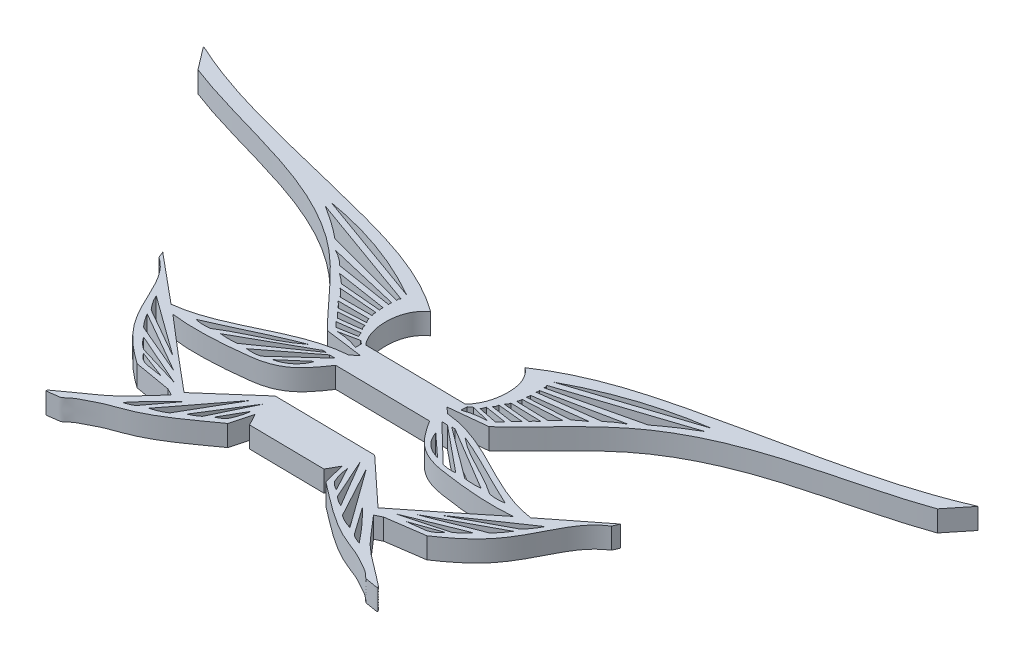
SolidWorks part; units mm, degrees
ref_plane "前视基准面" through (0, 0, 0) normal (0, 0, 1) x (1, 0, 0)
ref_plane "上视基准面" through (0, 0, 0) normal (0, 1, 0) x (1, 0, 0)
ref_plane "右视基准面" through (0, 0, 0) normal (1, 0, 0) x (0, 0, -1)
other "Configuration Table"
sketch "草图1" plane through (0, 0, 0) normal (0, 1, 0) x (1, 0, 0)
  line L0 (-16.1038, -29.8984) -> (-14.4909, -30.7553)
  line L1 (55.2168, 449.012) -> (841.2168, 449.012) construction
  line L2 (11.0888, 44.2891) -> (8.5696, -134.0017) construction
  line L3 (-35.1828, 28.1784) -> (-7.0967, 18.0952)
  line L4 (-27.2263, 21.1019) -> (-7.0967, 15.7486)
  line L6 (-21.1398, 16.1529) -> (-7.0967, 13.8965)
  line L7 (-24.774, 18.7977) -> (-7.2128, 14.6629)
  line L9 (-17.2033, 12.6101) -> (-7.0967, 11.7044)
  line L10 (-19.6184, 14.5422) -> (-7.2128, 12.6101)
  line L12 (-14.5684, 9.685) -> (-6.8789, 9.685)
  line L14 (-12.5975, 7.1733) -> (-6.0336, 7.5988)
  line L15 (-14.0695, 8.6454) -> (-6.577, 8.6454)
  line L17 (-10.5619, 5.0026) -> (-5.128, 5.6567)
  line L18 (-36.8477, -11.9893) -> (-22.4144, -22.4499)
  line L19 (-8.7638, 2.9366) -> (-4.2223, 3.7347)
  line L20 (-7.73, 2.2229) -> (-3.1356, 3.1712)
  line L21 (-16.4155, 11.532) -> (-7.0967, 10.7585)
  line L22 (-11.8701, 6.3108) -> (-5.6512, 6.7536)
  line L23 (-9.9443, 4.1171) -> (-4.6248, 4.8014)
  line L24 (-3.1356, 3.1712) -> (-2.3162, 2.539)
  line L25 (-2.3162, 2.539) -> (-2.3162, 1.0903)
  line L27 (-22.4144, -22.4499) -> (-34.4652, -15.5737)
  line L28 (-21.2778, -12.1694) -> (-5.6197, -3.4096)
  line L29 (-5.6197, -3.4096) -> (-4.7779, -3.4096)
  line L30 (-4.7779, -3.4096) -> (-17.294, -12.1857)
  line L32 (-15.0605, -12.1694) -> (-3.9079, -3.5602)
  line L33 (-3.9079, -3.5602) -> (-2.5338, -3.5602)
  line L34 (-2.5338, -3.5602) -> (-11.7753, -11.9893)
  line L35 (-9.6963, -11.3316) -> (-4.2223, -6.5835)
  line L36 (-34.191, -16.8125) -> (-19.1525, -25.4537)
  line L37 (-19.1525, -25.4537) -> (-31.8012, -20.077)
  line L38 (-29.805, -22.0591) -> (-16.8258, -27.7612)
  line L39 (-16.8258, -27.7612) -> (-27.2263, -24.6296)
  line L40 (-26.4037, -25.4537) -> (-19.6184, -28.0409)
  line L41 (-19.6184, -28.0409) -> (-23.7534, -27.401)
  line L42 (-3.9079, -22.4499) -> (-14.4158, -36.1706)
  line L43 (-16.4882, -37.1375) -> (-11.4591, -30.4187)
  line L44 (-8.6676, -32.8615) -> (-1.5765, -21.5816)
  line L45 (-4.7779, -30.2112) -> (-1.5765, -24.6296)
  line L46 (-6.3514, -31.4736) -> (-1.5765, -21.5816)
  line L47 (-10.9556, -34.6619) -> (-3.9079, -22.4499)
  line L48 (-45.0523, -2.2183) -> (-44.4505, -3.7232)
  line L49 (65.8936, -3.7859) -> (65.2495, -5.2733)
  line L50 (30.8938, -35.2532) -> (24.1939, -22.847)
  line L51 (26.3815, -31.9361) -> (21.8881, -21.9131)
  line L52 (24.8443, -30.6297) -> (21.8019, -24.9599)
  line L53 (28.6575, -33.3889) -> (21.8881, -21.9131)
  line L54 (36.3543, -37.8842) -> (31.5169, -31.026)
  line L55 (24.1939, -22.847) -> (34.31, -36.8591)
  line L56 (39.7402, -28.8797) -> (43.8916, -28.3568)
  line L57 (46.5959, -26.4851) -> (39.7402, -28.8797)
  line L58 (36.9566, -28.5211) -> (47.4415, -25.6846)
  line L59 (50.0918, -23.188) -> (36.9566, -28.5211)
  line L60 (39.3476, -26.2803) -> (52.1431, -21.2632)
  line L61 (54.6242, -18.0675) -> (39.3476, -26.2803)
  line L62 (30.2941, -11.8967) -> (24.9565, -6.9958)
  line L63 (23.3541, -3.926) -> (32.3538, -12.6128)
  line L64 (24.7277, -3.9648) -> (23.3541, -3.926)
  line L65 (35.6326, -12.8857) -> (24.7277, -3.9648)
  line L66 (25.6016, -3.8389) -> (37.8647, -12.9651)
  line L67 (26.4431, -3.8627) -> (25.6016, -3.8389)
  line L68 (41.8474, -13.0614) -> (26.4431, -3.8627)
  line L69 (42.6931, -23.3698) -> (54.9333, -16.8369)
  line L70 (23.309, 2.1769) -> (23.268, 0.7288)
  line L71 (24.1458, 2.7857) -> (23.309, 2.1769)
  line L72 (30.9785, 3.5389) -> (25.6806, 4.3732)
  line L73 (32.9655, 5.6773) -> (26.7617, 6.2956)
  line L74 (37.6567, 10.768) -> (28.3198, 10.2581)
  line L75 (28.7116, 1.708) -> (24.1458, 2.7857)
  line L76 (29.7652, 2.3922) -> (25.2481, 3.3183)
  line L77 (57.4161, -13.3212) -> (42.6931, -23.3698)
  line L78 (31.6209, 4.4066) -> (26.2077, 5.2139)
  line L79 (35.2301, 7.9488) -> (27.7406, 8.1605)
  line L80 (33.717, 6.5189) -> (27.1678, 7.1297)
  line L81 (35.7582, 8.9739) -> (28.0717, 9.1911)
  line L82 (40.9434, 13.6864) -> (28.4881, 12.1056)
  line L83 (38.4747, 11.8234) -> (28.3465, 11.2036)
  line L84 (46.2171, 17.7946) -> (28.5461, 14.1576)
  line L85 (42.5096, 15.2535) -> (28.4084, 13.3948)
  line L86 (48.7336, 20.0286) -> (28.4607, 15.2462)
  line L87 (56.8868, 26.8775) -> (28.527, 17.5919)
  line L88 (36.1745, -30.637) -> (34.538, -31.4481)
  line L89 (-1.5765, 2.8276) -> (22.5777, 2.4863)
  line L90 (-1.5765, -1.2849) -> (0, 0)
  line L91 (22.4615, -1.6245) -> (20.9219, -0.2956)
  line L92 (1.0655, -27.5848) -> (19.0775, -27.8393)
  line L93 (-1.5765, -1.2849) -> (-0.9859, -4.9581)
  line L94 (-0.9859, -4.9581) -> (21.7673, -5.2796)
  line L95 (-1.8489, -18.5408) -> (22.2462, -18.8813)
  spline S0 degree 3 poles (-0.7293, 17.4834) (-3.1453, 15.714) (-4.7785, 10.3382) (-3.3083, 4.8102) (-1.5765, 2.8276) knots 0 0 0 0 0.513587 1 1 1 1
  spline S1 degree 3 poles (-0.7293, 17.4834) (-9.9253, 24.1606) (-25.7873, 28.7225) (-53.9047, 35.5722) (-71.2957, 39.8733) (-82.7877, 45.2469) knots 0 0 0 0 0.38436 0.564437 1 1 1 1
  spline S2 degree 1 poles (-82.7877, 45.2469) (-78.5986, 39.7435) knots 0 0 1 1
  spline S3 degree 3 poles (-78.5986, 39.7435) (-66.4134, 35.0224) (-47.7039, 31.6735) (-23.6611, 18.3068) (-14.9849, 6.9582) (-9.1077, 1.2196) knots 0 0 0 0 0.482736 0.695059 1 1 1 1
  spline S4 degree 1 poles (-9.1077, 1.2196) (0, 0) knots 0 0 1 1
  spline S5 degree 3 poles (-1.5765, -1.2849) (-12.9973, -2.0584) (-21.9304, -10.6867) (-33.3037, -11.9893) knots 0 0 0 0 1 1 1 1
  spline S6 degree 1 poles (-33.3037, -11.9893) (-45.0523, -2.2183) knots 0 0 1 1
  spline S7 degree 3 poles (-44.4505, -3.7232) (-41.0317, -6.0491) (-38.1927, -12.2635) (-33.4529, -21.8525) (-28.0626, -26.2146) (-25.0609, -28.3545) knots 0 0 0 0 0.362458 0.649175 1 1 1 1
  spline S8 degree 1 poles (-25.0609, -28.3545) (-16.1038, -29.8984) knots 0 0 1 1
  spline S9 degree 3 poles (-14.4909, -30.7553) (-20.8847, -37.4993) (-18.448, -36.2364) (-31.1895, -45.0289) (-26.994, -44.4382) (-27.3576, -44.6482) (-25.2489, -42.8456) (-23.406, -42.0441) (-20.5956, -40.4291) (-12.6121, -38.0713) (-6.5286, -33.1947) (-1.8489, -29.8984) knots 0 0 0 0 0.138213 0.158314 0.168524 0.240317 0.287507 0.34345 0.409539 0.53848 1 1 1 1
  spline S10 degree 1 poles (-1.8489, -29.8984) (-0.4456, -24.7424) knots 0 0 1 1
  spline S11 degree 1 poles (-0.4456, -24.7424) (1.0655, -27.5848) knots 0 0 1 1
  spline S12 degree 3 poles (-30.9971, -13.8611) (-25.5017, -14.5037) (-17.1294, -14.0002) (-9.1527, -12.8696) (-4.2716, -9.7226) (-2.4036, -7.0417) (-0.9859, -4.9581) knots 0 0 0 0 0.52181 0.750761 0.787531 1 1 1 1
  spline S13 degree 2 poles (-30.9971, -13.8611) (-22.2983, -21.3772) (-13.459, -28.7273) knots 0 0 0 1 1 1
  spline S14 degree 1 poles (-13.459, -28.7273) (-1.8489, -18.5408) knots 0 0 1 1
  spline S15 degree 2 poles (-35.1828, 28.1784) (-20.2481, 25.6428) (-7.0967, 18.0952) knots 0 0 0 1 1 1
  spline S16 degree 2 poles (-35.1828, 26.7484) (-31.0116, 24.2005) (-27.2263, 21.1019) knots 0 0 0 1 1 1
  spline S17 degree 1 poles (-35.1828, 26.7484) (-6.9624, 16.5949) knots 0 0 1 1
  spline S18 degree 2 poles (-6.9624, 16.5949) (-7.3866, 16.2141) (-7.0967, 15.7486) knots 0 0 0 1 1 1
  spline S19 degree 2 poles (-7.2128, 14.6629) (-7.4298, 14.2488) (-7.0967, 13.8965) knots 0 0 0 1 1 1
  spline S20 degree 2 poles (-7.2128, 12.6101) (-7.3464, 12.1186) (-7.0967, 11.7044) knots 0 0 0 1 1 1
  spline S21 degree 2 poles (-7.0967, 10.7585) (-7.2103, 10.1725) (-6.8789, 9.685) knots 0 0 0 1 1 1
  spline S22 degree 2 poles (-6.577, 8.6454) (-6.5886, 7.9876) (-6.0336, 7.5988) knots 0 0 0 1 1 1
  spline S23 degree 2 poles (-5.6512, 6.7536) (-5.724, 6.0801) (-5.128, 5.6567) knots 0 0 0 1 1 1
  spline S24 degree 3 poles (-27.2263, -12.1694) (-20.9503, -9.5199) (-14.926, -6.273) (-8.5381, -3.8842) knots 0 0 0 0 1 1 1 1
  spline S25 degree 3 poles (-8.5381, -3.8842) (-13.1033, -7.473) (-18.7599, -9.1308) (-23.5809, -12.2986) knots 0 0 0 0 1 1 1 1
  spline S26 degree 2 poles (-15.0605, -12.1694) (-13.3879, -12.4146) (-11.7753, -11.9893) knots 0 0 0 1 1 1
  spline S27 degree 2 poles (-21.2778, -12.1694) (-19.2849, -12.4221) (-17.294, -12.1857) knots 0 0 0 1 1 1
  spline S28 degree 2 poles (-27.2263, -12.1694) (-25.4052, -12.5568) (-23.5809, -12.2986) knots 0 0 0 1 1 1
  spline S29 degree 2 poles (-4.2223, -6.5835) (-5.6759, -10.4126) (-9.6963, -11.3316) knots 0 0 0 1 1 1
  spline S30 degree 2 poles (-24.774, 18.7977) (-22.7376, 17.7531) (-21.1398, 16.1529) knots 0 0 0 1 1 1
  spline S31 degree 2 poles (-19.6184, 14.5422) (-18.3287, 13.6785) (-17.2033, 12.6101) knots 0 0 0 1 1 1
  spline S32 degree 2 poles (-16.4155, 11.532) (-15.3902, 10.7078) (-14.5684, 9.685) knots 0 0 0 1 1 1
  spline S33 degree 2 poles (-14.0695, 8.6454) (-13.2207, 8.0185) (-12.5975, 7.1733) knots 0 0 0 1 1 1
  spline S34 degree 2 poles (-11.8701, 6.3108) (-11.1648, 5.7068) (-10.5619, 5.0026) knots 0 0 0 1 1 1
  spline S35 degree 2 poles (-9.9443, 4.1171) (-9.3284, 3.5521) (-8.7638, 2.9366) knots 0 0 0 1 1 1
  spline S36 degree 2 poles (-7.73, 2.2229) (-4.9085, 2.1238) (-2.3162, 1.0903) knots 0 0 0 1 1 1
  spline S37 degree 2 poles (-36.8477, -11.9893) (-35.9291, -13.9781) (-34.4652, -15.5737) knots 0 0 0 1 1 1
  spline S38 degree 2 poles (-34.191, -16.8125) (-33.1483, -18.558) (-31.8012, -20.077) knots 0 0 0 1 1 1
  spline S39 degree 2 poles (-29.805, -22.0591) (-28.7536, -23.5703) (-27.2263, -24.6296) knots 0 0 0 1 1 1
  spline S40 degree 2 poles (-26.4037, -25.4537) (-25.455, -26.96) (-23.7534, -27.401) knots 0 0 0 1 1 1
  spline S41 degree 2 poles (-14.4158, -36.1706) (-12.5462, -35.7028) (-10.9556, -34.6619) knots 0 0 0 1 1 1
  spline S42 degree 2 poles (-8.6676, -32.8615) (-7.3979, -32.3437) (-6.3514, -31.4736) knots 0 0 0 1 1 1
  spline S43 degree 2 poles (-4.7779, -30.2112) (-3.5827, -29.7227) (-2.7802, -28.7273) knots 0 0 0 1 1 1
  spline S44 degree 2 poles (-11.4591, -30.4187) (-15.3686, -34.0532) (-18.795, -38.1409) knots 0 0 0 1 1 1
  spline S45 degree 2 poles (-18.795, -38.1409) (-17.5646, -37.8119) (-16.4882, -37.1375) knots 0 0 0 1 1 1
  spline S46 degree 2 poles (-1.5765, -24.6296) (-1.8193, -26.8002) (-2.7802, -28.7273) knots 0 0 0 1 1 1
  spline S47 degree 2 poles (21.8019, -24.9599) (21.9833, -27.1365) (22.8893, -29.09) knots 0 0 0 1 1 1
  spline S48 degree 2 poles (38.6318, -38.9523) (37.4111, -38.5887) (36.3543, -37.8842) knots 0 0 0 1 1 1
  spline S49 degree 2 poles (31.5169, -31.026) (35.3222, -34.7695) (38.6318, -38.9523) knots 0 0 0 1 1 1
  spline S50 degree 2 poles (24.8443, -30.6297) (23.6634, -30.1076) (22.8893, -29.09) knots 0 0 0 1 1 1
  spline S51 degree 2 poles (28.6575, -33.3889) (27.403, -32.8355) (26.3815, -31.9361) knots 0 0 0 1 1 1
  spline S52 degree 2 poles (34.31, -36.8591) (32.4544, -36.3387) (30.8938, -35.2532) knots 0 0 0 1 1 1
  spline S53 degree 2 poles (46.5959, -26.4851) (45.605, -27.9641) (43.8916, -28.3568) knots 0 0 0 1 1 1
  spline S54 degree 2 poles (50.0918, -23.188) (48.998, -24.6689) (47.4415, -25.6846) knots 0 0 0 1 1 1
  spline S55 degree 2 poles (54.6242, -18.0675) (53.5327, -19.7828) (52.1431, -21.2632) knots 0 0 0 1 1 1
  spline S56 degree 2 poles (57.4161, -13.3212) (56.4417, -15.2833) (54.9333, -16.8369) knots 0 0 0 1 1 1
  spline S57 degree 2 poles (28.7116, 1.708) (25.8885, 1.6886) (23.268, 0.7288) knots 0 0 0 1 1 1
  spline S58 degree 2 poles (30.9785, 3.5389) (30.3469, 2.9915) (29.7652, 2.3922) knots 0 0 0 1 1 1
  spline S59 degree 2 poles (32.9655, 5.6773) (32.2435, 5.0935) (31.6209, 4.4066) knots 0 0 0 1 1 1
  spline S60 degree 2 poles (35.2301, 7.9488) (34.3639, 7.3462) (33.717, 6.5189) knots 0 0 0 1 1 1
  spline S61 degree 2 poles (37.6567, 10.768) (36.6085, 9.9731) (35.7582, 8.9739) knots 0 0 0 1 1 1
  spline S62 degree 2 poles (40.9434, 13.6864) (39.6298, 12.8595) (38.4747, 11.8234) knots 0 0 0 1 1 1
  spline S63 degree 2 poles (46.2171, 17.7946) (44.152, 16.808) (42.5096, 15.2535) knots 0 0 0 1 1 1
  spline S64 degree 2 poles (24.9565, -6.9958) (26.3014, -10.8644) (30.2941, -11.8967) knots 0 0 0 1 1 1
  spline S65 degree 2 poles (47.7935, -13.2294) (45.9621, -13.5652) (44.1459, -13.2556) knots 0 0 0 1 1 1
  spline S66 degree 2 poles (41.8474, -13.0614) (39.8481, -13.2577) (37.8647, -12.9651) knots 0 0 0 1 1 1
  spline S67 degree 2 poles (35.6326, -12.8857) (33.9537, -13.0835) (32.3538, -12.6128) knots 0 0 0 1 1 1
  spline S68 degree 3 poles (29.3469, -4.4195) (33.8089, -8.1358) (39.4163, -9.9528) (44.1459, -13.2556) knots 0 0 0 0 1 1 1 1
  spline S69 degree 3 poles (47.7935, -13.2294) (41.5949, -10.4036) (35.6648, -6.9878) (29.3469, -4.4195) knots 0 0 0 0 1 1 1 1
  spline S70 degree 2 poles (26.7617, 6.2956) (26.8154, 5.6203) (26.2077, 5.2139) knots 0 0 0 1 1 1
  spline S71 degree 2 poles (27.7406, 8.1605) (27.7335, 7.5027) (27.1678, 7.1297) knots 0 0 0 1 1 1
  spline S72 degree 2 poles (28.3198, 10.2581) (28.4167, 9.6691) (28.0717, 9.1911) knots 0 0 0 1 1 1
  spline S73 degree 2 poles (28.4881, 12.1056) (28.6078, 11.6106) (28.3465, 11.2036) knots 0 0 0 1 1 1
  spline S74 degree 2 poles (28.5461, 14.1576) (28.7513, 13.7375) (28.4084, 13.3948) knots 0 0 0 1 1 1
  spline S75 degree 2 poles (28.3504, 16.0959) (28.7636, 15.7033) (28.4607, 15.2462) knots 0 0 0 1 1 1
  spline S76 degree 1 poles (56.8464, 25.4481) (28.3504, 16.0959) knots 0 0 1 1
  spline S77 degree 2 poles (56.8464, 25.4481) (52.6049, 23.019) (48.7336, 20.0286) knots 0 0 0 1 1 1
  spline S78 degree 2 poles (56.8868, 26.8775) (41.8864, 24.7649) (28.527, 17.5919) knots 0 0 0 1 1 1
  spline S79 degree 1 poles (33.5639, -29.3917) (22.2462, -18.8813) knots 0 0 1 1
  spline S80 degree 2 poles (51.515, -15.027) (42.6074, -22.2943) (33.5639, -29.3917) knots 0 0 0 1 1 1
  spline S81 degree 3 poles (51.515, -15.027) (46.0037, -15.5141) (37.6489, -14.7742) (29.7073, -13.4187) (24.9171, -10.1351) (23.1256, -7.4024) (21.7673, -5.2796) knots 0 0 0 0 0.52181 0.750761 0.787531 1 1 1 1
  spline S82 degree 1 poles (20.6683, -25.0407) (19.0775, -27.8393) knots 0 0 1 1
  spline S83 degree 1 poles (21.9253, -30.2343) (20.6683, -25.0407) knots 0 0 1 1
  spline S84 degree 3 poles (34.538, -31.4481) (40.7387, -38.37) (38.3387, -37.0388) (50.8267, -46.1878) (46.6495, -45.4788) (47.0071, -45.6989) (44.9501, -43.8375) (43.1306, -42.9842) (40.367, -41.2905) (32.4533, -38.7081) (26.51, -33.6615) (21.9253, -30.2343) knots 0 0 0 0 0.138213 0.158314 0.168524 0.240317 0.287507 0.34345 0.409539 0.53848 1 1 1 1
  spline S85 degree 1 poles (45.1717, -29.3469) (36.1745, -30.637) knots 0 0 1 1
  spline S86 degree 3 poles (65.2495, -5.2733) (61.7663, -7.5016) (58.7529, -13.6333) (53.744, -23.0846) (48.2326, -27.2926) (45.1717, -29.3469) knots 0 0 0 0 0.362458 0.649175 1 1 1 1
  spline S87 degree 1 poles (53.8736, -13.2211) (65.8936, -3.7859) knots 0 0 1 1
  spline S88 degree 3 poles (22.4615, -1.6245) (33.8558, -2.7204) (42.5416, -11.5977) (53.8736, -13.2211) knots 0 0 0 0 1 1 1 1
  spline S89 degree 1 poles (30.0604, 0.6662) (20.9219, -0.2956) knots 0 0 1 1
  spline S90 degree 3 poles (100.612, 37.2113) (88.2983, 32.8364) (69.5017, 30.0175) (45.0908, 17.3354) (36.0974, 6.2364) (30.0604, 0.6662) knots 0 0 0 0 0.482736 0.695059 1 1 1 1
  spline S91 degree 1 poles (104.955, 42.5942) (100.612, 37.2113) knots 0 0 1 1
  spline S92 degree 3 poles (22.1449, 17.1602) (31.5259, 23.5749) (47.5104, 27.6868) (75.8101, 33.7394) (93.3157, 37.5474) (104.955, 42.5942) knots 0 0 0 0 0.38436 0.564437 1 1 1 1
  spline S93 degree 3 poles (22.1449, 17.1602) (24.5099, 15.3232) (25.9906, 9.9034) (24.3648, 4.4192) (22.5777, 2.4863) knots 0 0 0 0 0.513587 1 1 1 1
  spline S94 degree 2 poles (-4.6248, 4.8014) (-4.4766, 4.2472) (-4.2223, 3.7347) knots 0 0 0 1 1 1
  spline S95 degree 2 poles (25.6806, 4.3732) (25.5562, 3.8046) (25.2481, 3.3183) knots 0 0 0 1 1 1
  point P159 (0, 0)
extrude "凸台-拉伸2" add sketch "草图1" along normal blind 5
